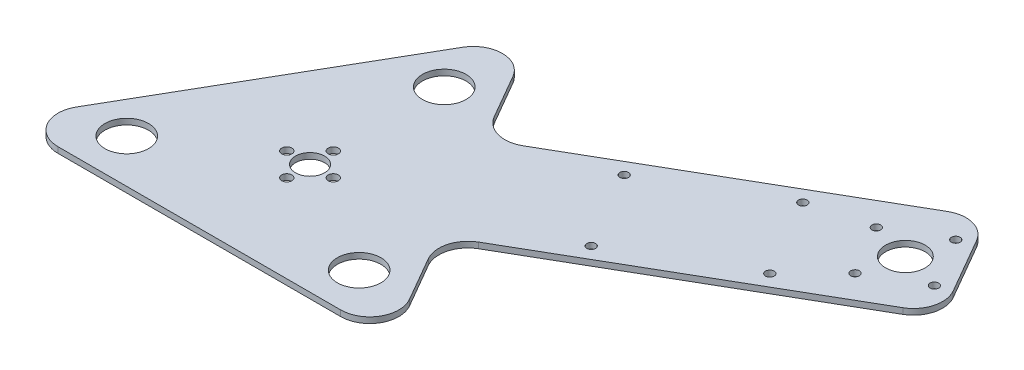
SolidWorks part; units mm, degrees
ref_plane "Front Plane" through (0, 0, 0) normal (0, 0, 1) x (1, 0, 0)
ref_plane "Top Plane" through (0, 0, 0) normal (0, 1, 0) x (1, 0, 0)
ref_plane "Right Plane" through (0, 0, 0) normal (1, 0, 0) x (0, 0, -1)
sketch "Sketch1" plane through (0, 0, 0) normal (0, 1, 0) x (1, 0, 0)
  line L0 (0, 0) -> (0, 85.65) construction
  line L1 (0, 0) -> (-86.4758, -49.9268) construction
  line L2 (0, 0) -> (78.7364, -45.4585) construction
  line L3 (0, 46.188) -> (-40, -23.094) construction
  line L4 (-40, -23.094) -> (40, -23.094) construction
  line L5 (40, -23.094) -> (0, 46.188) construction
  line L6 (0, 76.188) -> (-65.9808, -38.094)
  line L7 (-65.9808, -38.094) -> (65.9808, -38.094)
  line L8 (65.9808, -38.094) -> (0, 76.188)
  circle A0 centre (0, 46.188) radius 7.5
  circle A1 centre (-40, -23.094) radius 7.5
  circle A2 centre (40, -23.094) radius 7.5
  circle A3 centre (0, 0) radius 5
  dimension "D6" = 15
  dimension "D8" = 10
  dimension "D1" = 120
  dimension "D2" = 120
  dimension "D3" = 80
  dimension "D4" = 80
  dimension "D5" = 80
  dimension "D7" = 15
extrude "Boss-Extrude1" add sketch "Sketch1" along normal blind 2
sketch "Sketch2" plane through (0, 2, 0) normal (0, 1, 0) x (1, 0, 0)
  line L0 (-65.9808, -38.094) -> (-40, -23.094) construction
  line L1 (-40, -23.094) -> (205.1906, 118.4669) construction
  line L2 (43.4904, 0.8605) -> (22.4904, 37.2335)
  line L3 (43.4904, 0.8605) -> (153.3942, 64.3135)
  line L4 (22.4904, 37.2335) -> (132.3942, 100.6865)
  line L5 (153.3942, 64.3135) -> (132.3942, 100.6865)
  line L6 (65.9808, -38.094) -> (0, 76.188) construction
  dimension "D1" = 165
  dimension "D2" = 21
  dimension "D3" = 21
extrude "Boss-Extrude2" add sketch "Sketch2" against normal blind 2
fillet "Fillet1" radius 10 7 edges at (132.3942, 1, -100.6865) (153.3942, 1, -64.3135) (22.4904, 1, -37.2335) (43.4904, 1, -0.8605) (0, 1, -76.188) (65.9808, 1, 38.094) (-65.9808, 1, 38.094)
sketch "Sketch3" plane through (0, 2, 0) normal (0, 1, 0) x (1, 0, 0)
  line L0 (142.8942, 82.5) -> (111.0381, 64.1079) construction
  line L1 (148.3942, 72.9737) -> (137.3942, 92.0263) construction
  line L2 (116.0233, 99.0418) -> (149.0716, 41.8004) construction
  line L3 (52.1506, 5.8605) -> (144.7339, 59.3135) construction
  circle A0 centre (129.9038, 75) radius 6.8
  point P8 (129.9038, 75)
  dimension "D2" = 13.6
  dimension "D1" = 15
extrude "Cut-Extrude1" cut sketch "Sketch3" against normal blind 10
sketch "Sketch4" plane through (0, 2, 0) normal (0, 1, 0) x (1, 0, 0)
  circle A0 centre (133.5641, 88.6603) radius 1.5
  circle A1 centre (116.2436, 78.6603) radius 1.5
  circle A2 centre (126.2436, 61.3397) radius 1.5
  circle A3 centre (143.5641, 71.3397) radius 1.5
  dimension "D5" = 3
  dimension "D6" = 3
  dimension "D7" = 3
  dimension "D8" = 3
extrude "Cut-Extrude2" cut sketch "Sketch4" against normal blind 10
sketch "Sketch5" plane through (0, 2, 0) normal (0, 1, 0) x (1, 0, 0)
  line L0 (33.2367, 37.0871) -> (102.2587, 76.937) construction
  line L1 (49.5114, 10.6876) -> (120.3495, 51.5859) construction
  line L2 (52.1506, 5.8605) -> (144.7339, 59.3135) construction
  line L3 (123.7339, 95.6865) -> (31.1506, 42.2335) construction
  line L4 (148.3942, 72.9737) -> (137.3942, 92.0263) construction
  circle A0 centre (96.173, 73.4234) radius 1.5
  circle A1 centre (57.2019, 50.9234) radius 1.5
  circle A2 centre (111.673, 46.5766) radius 1.5
  circle A3 centre (72.7019, 24.0766) radius 1.5
  dimension "D7" = 3
  dimension "D8" = 3
  dimension "D9" = 3
  dimension "D10" = 3
  dimension "D1" = 5.5
  dimension "D2" = 5.5
  dimension "D3" = 45
  dimension "D4" = 45
  dimension "D5" = 90
  dimension "D6" = 90
extrude "Cut-Extrude3" cut sketch "Sketch5" against normal blind 10
sketch "Sketch6" plane through (0, 2, 0) normal (0, 1, 0) x (1, 0, 0)
  circle A1 centre (0, 8) radius 1.75
  circle A2 centre (8, 0) radius 1.75
  circle A3 centre (0, -8) radius 1.75
  circle A4 centre (-8, 0) radius 1.75
  dimension "D2" = 3.5
extrude "Cut-Extrude4" cut sketch "Sketch6" against normal through all
